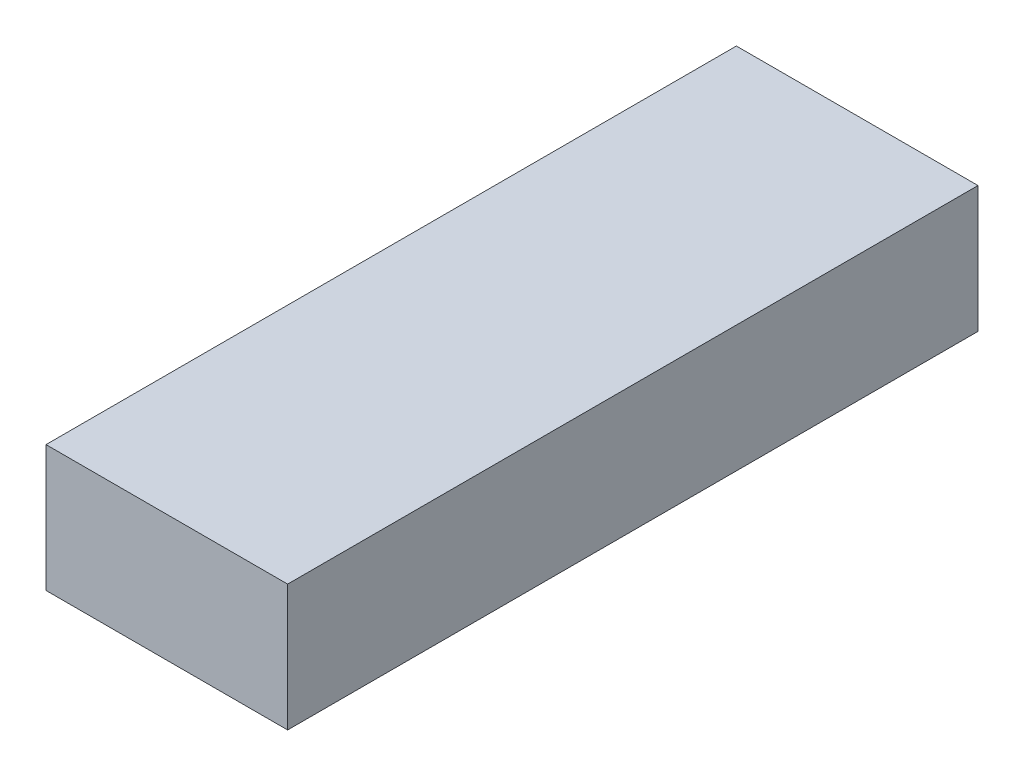
SolidWorks part; units mm, degrees
ref_plane "Front Plane" through (0, 0, 0) normal (0, 0, 1) x (1, 0, 0)
ref_plane "Top Plane" through (0, 0, 0) normal (0, 1, 0) x (1, 0, 0)
ref_plane "Right Plane" through (0, 0, 0) normal (1, 0, 0) x (0, 0, -1)
sketch "Sketch1" plane through (0, 0, 0) normal (0, 0, 1) x (1, 0, 0)
  line L1 (0, 0) -> (8.89, 0)
  line L2 (0, 0) -> (0, 4.6482)
  line L3 (0, 4.6482) -> (8.89, 4.6482)
  line L4 (8.89, 0) -> (8.89, 4.6482)
  dimension "D1" = 4.6482
  dimension "D2" = 8.89
extrude "Boss-Extrude1" add sketch "Sketch1" along normal blind 25.4
